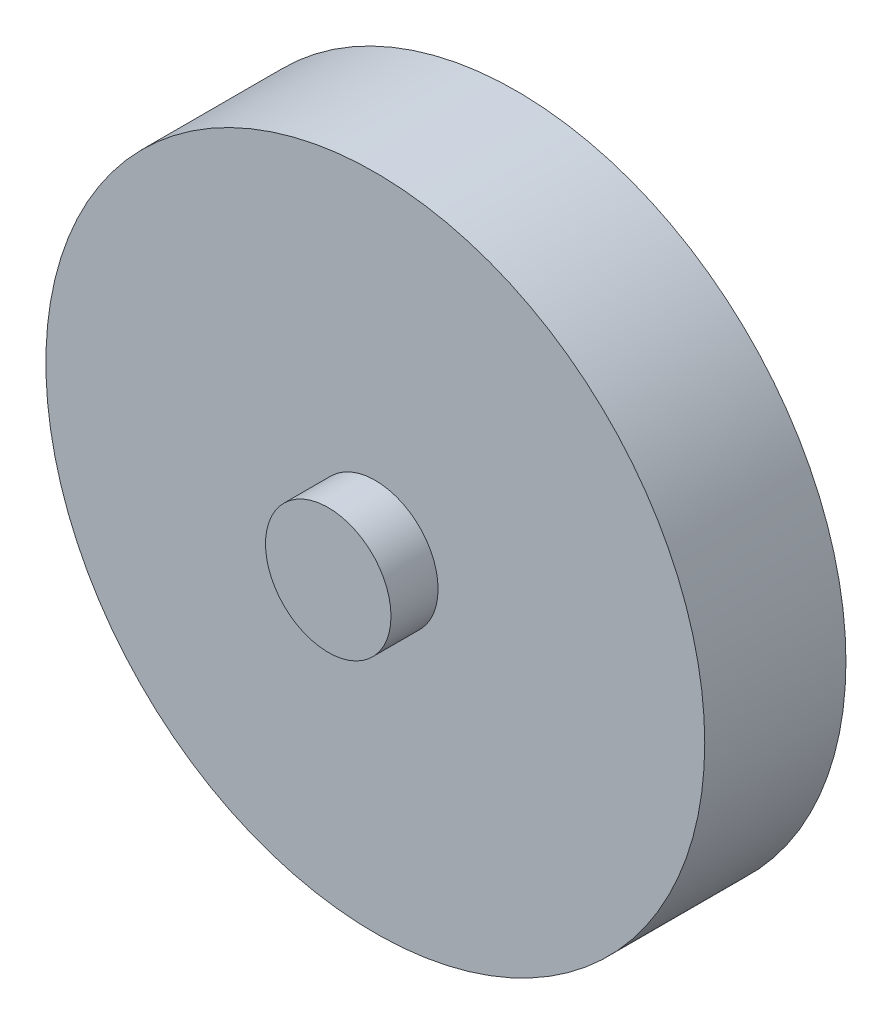
SolidWorks part; units mm, degrees
ref_plane "前视基准面" through (0, 0, 0) normal (0, 0, 1) x (1, 0, 0)
ref_plane "上视基准面" through (0, 0, 0) normal (0, 1, 0) x (1, 0, 0)
ref_plane "右视基准面" through (0, 0, 0) normal (1, 0, 0) x (0, 0, -1)
other "Configuration Table"
sketch "草图1" plane through (0, 0, 0) normal (0, 0, 1) x (1, 0, 0)
  circle A0 centre (0, 0) radius 8
extrude "凸台-拉伸1" add sketch "草图1" along normal blind 24
sketch "草图2" plane through (0, 0, 0) normal (0, 0, 1) x (1, 0, 0)
  circle A0 centre (0, 0) radius 42
extrude "凸台-拉伸2" add sketch "草图2" along normal blind 18
